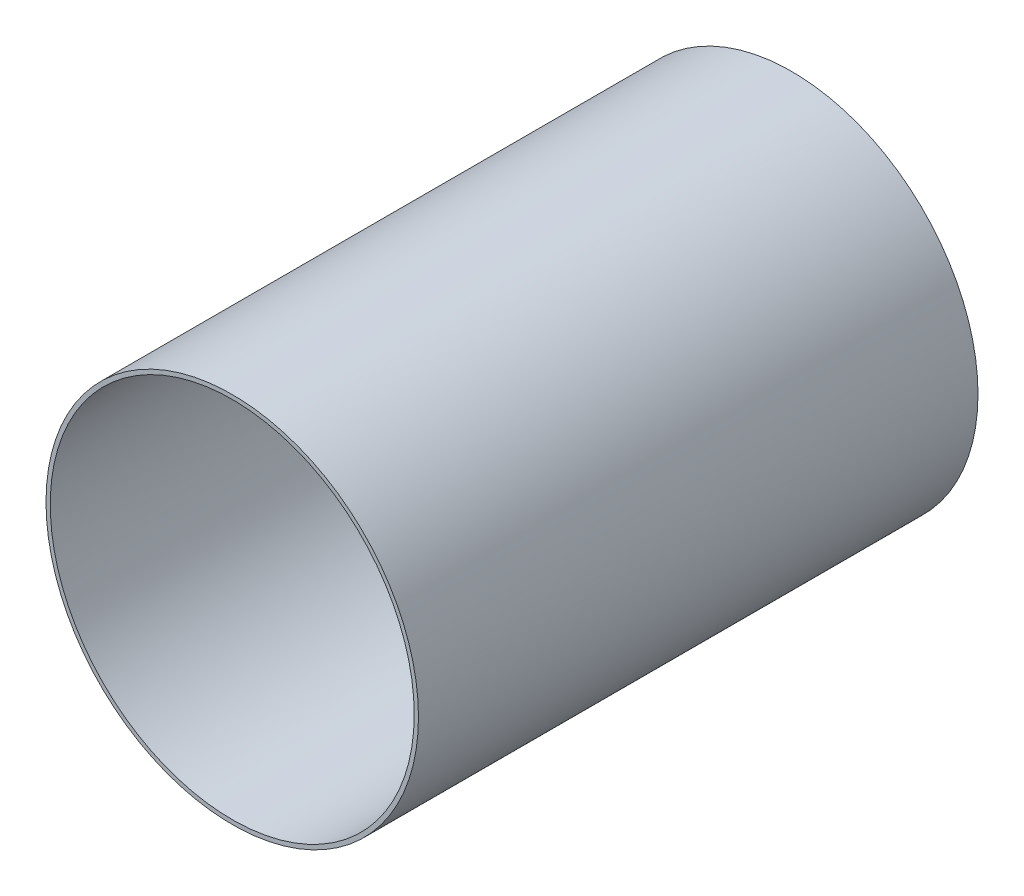
SolidWorks part; units mm, degrees
material "E-Glass Fiber"
ref_plane "Front Plane" through (0, 0, 0) normal (0, 0, 1) x (1, 0, 0)
ref_plane "Top Plane" through (0, 0, 0) normal (0, 1, 0) x (1, 0, 0)
ref_plane "Right Plane" through (0, 0, 0) normal (1, 0, 0) x (0, 0, -1)
sketch "Sketch1" plane through (0, 0, 0) normal (0, 0, 1) x (1, 0, 0)
  circle A0 centre (0, 0) radius 49.6697
  circle A1 centre (0, 0) radius 48.5394
  dimension "D1" = 99.3394
  dimension "D2" = 97.0788
extrude "Boss-Extrude1" add sketch "Sketch1" along normal blind 149.225
